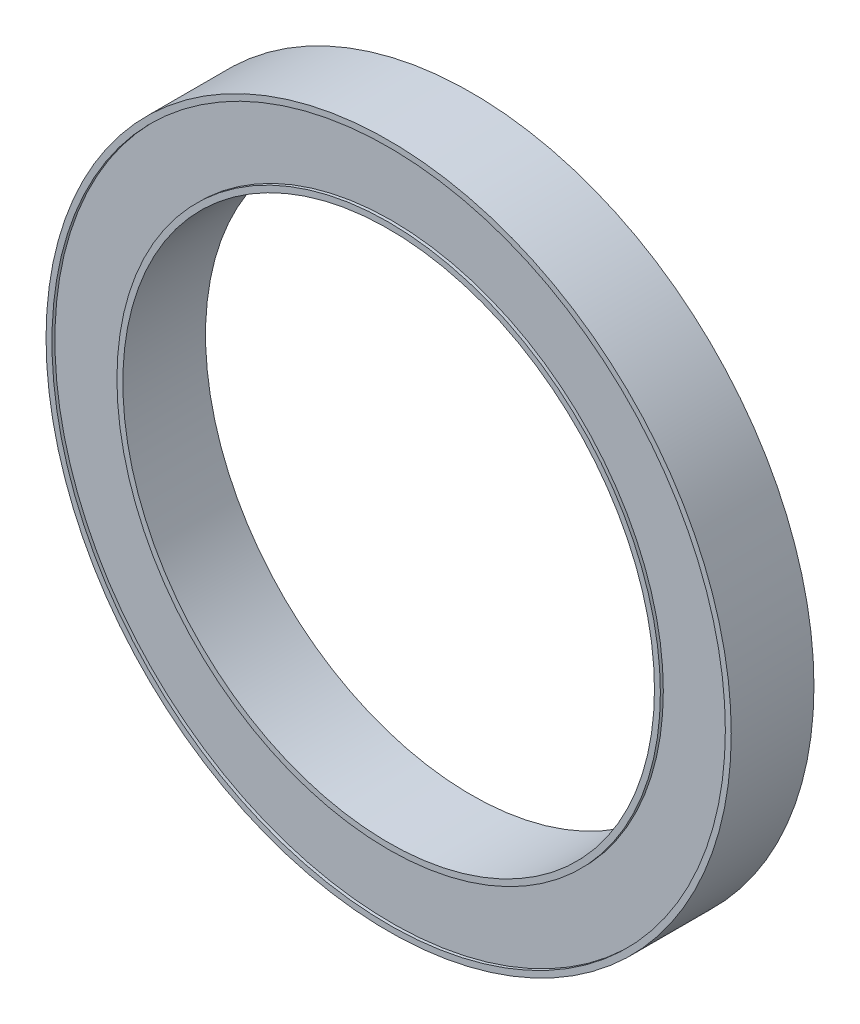
SolidWorks part; units mm, degrees
ref_plane "Front Plane" through (0, 0, 0) normal (0, 0, 1) x (1, 0, 0)
ref_plane "Top Plane" through (0, 0, 0) normal (0, 1, 0) x (1, 0, 0)
ref_plane "Right Plane" through (0, 0, 0) normal (1, 0, 0) x (0, 0, -1)
sketch "Sketch1" plane through (0, 0, 0) normal (0, 0, 1) x (1, 0, 0)
  circle A0 centre (0, 0) radius 22.5
  circle A1 centre (0, 0) radius 29
  dimension "D1" = 58
  dimension "D2" = 45
extrude "Boss-Extrude1" add sketch "Sketch1" along normal mid plane 7
sketch "Sketch2" plane through (0, 0, 3.5) normal (0, 0, 1) x (1, 0, 0)
  circle A2 centre (0, 0) radius 28.5
  circle A3 centre (0, 0) radius 28.5
  circle A5 centre (0, 0) radius 23
  circle A6 centre (0, 0) radius 23
  dimension "D1" = 0.5
  dimension "D2" = 0.5
extrude "Cut-Extrude1" cut sketch "Sketch2" against normal blind 0.25 contours A3 | A6
mirror "Mirror1" about plane through (0, 0, 0) normal (0, 0, 1) of "Cut-Extrude1"
equation "\"Bearing Internal 'd'\"= 45mm"
equation "\"Bearing External 'd'\"= 58mm"
equation "\"Bearing Width\"= 7mm"
equation "\"D1@Sketch1\"=\"Bearing External 'd'\"'''''''''"
equation "\"D2@Sketch1\"=\"Bearing Internal 'd'\"'''''''''"
equation "\"D1@Boss-Extrude1\"=\"Bearing Width\""
